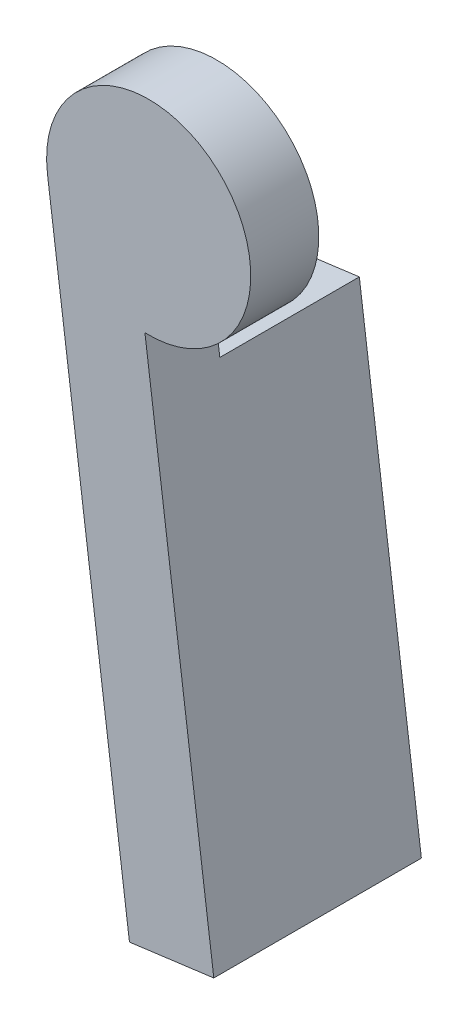
SolidWorks part; units mm, degrees
ref_plane "Front Plane" through (0, 0, 0) normal (0, 0, 1) x (1, 0, 0)
ref_plane "Top Plane" through (0, 0, 0) normal (0, 1, 0) x (1, 0, 0)
ref_plane "Right Plane" through (0, 0, 0) normal (1, 0, 0) x (0, 0, -1)
sketch "Sketch1" plane through (0, 0, 0) normal (0, 0, 1) x (1, 0, 0)
  circle A0 centre (0, 0) radius 19.05
  dimension "D1" = 38.1
extrude "Boss-Extrude1" add sketch "Sketch1" along normal blind 12.7
sketch "Sketch2" plane through (0, 0, 12.7) normal (0, 0, 1) x (1, 0, 0)
  line L0 (-18.8877, -2.4811) -> (-3.5875, -118.9555)
  line L1 (-3.5875, -118.9555) -> (12.1523, -116.8879)
  line L2 (12.1523, -116.8879) -> (-0.7015, -19.0371)
  line L3 (12.1523, -116.8879) -> (0.5737, -28.7451) construction
  circle A0 centre (0, 0) radius 19.05 construction
  arc A1 (-18.8877, -2.4811) -> (-0.7015, -19.0371) centre (0, 0) ccw
extrude "Boss-Extrude2" add sketch "Sketch2" against normal up to surface (12.7 mm away) up to face at (19.05, 0, 0)
sketch "Sketch3" plane through (0, 0, 0) normal (0, 0, -1) x (-1, 0, 0)
  line L0 (3.5875, -118.9555) -> (-12.1523, -116.8879)
  line L1 (3.5875, -118.9555) -> (15.1661, -30.8127)
  line L2 (-12.1523, -116.8879) -> (-0.5737, -28.7451)
  line L3 (15.1661, -30.8127) -> (-0.5737, -28.7451)
  line L4 (-0.5737, -28.7451) -> (15.1661, -30.8127) construction
extrude "Boss-Extrude3" add sketch "Sketch3" along normal blind 26.035
